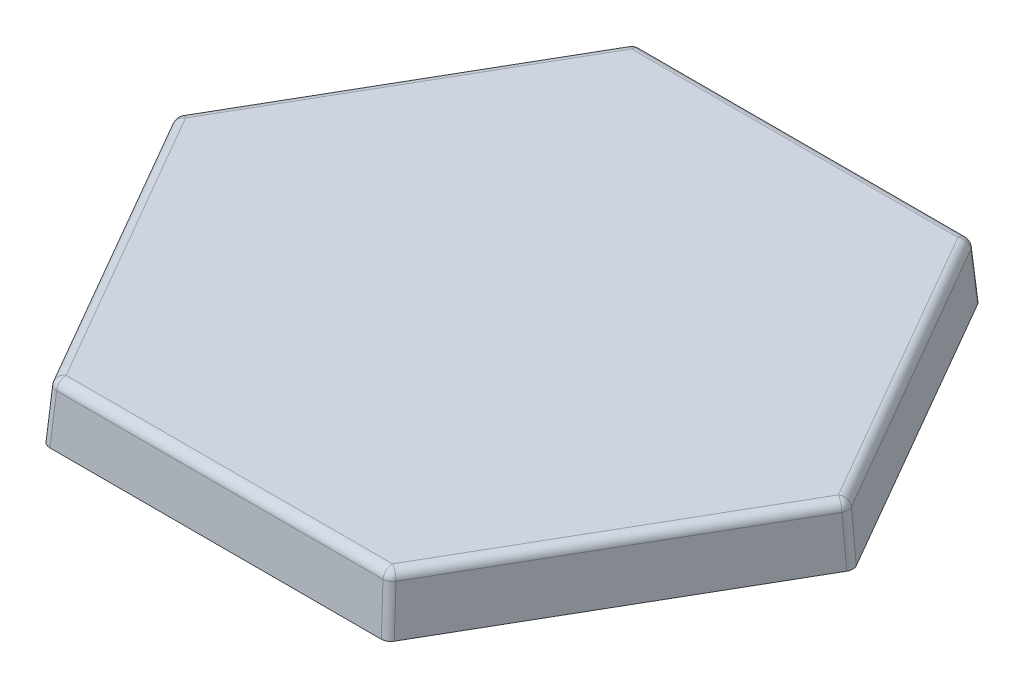
SolidWorks part; units mm, degrees
ref_plane "Front Plane" through (0, 0, 0) normal (0, 0, 1) x (1, 0, 0)
ref_plane "Top Plane" through (0, 0, 0) normal (0, 1, 0) x (1, 0, 0)
ref_plane "Right Plane" through (0, 0, 0) normal (1, 0, 0) x (0, 0, -1)
sketch "Sketch1" plane through (0, 0, 0) normal (0, 1, 0) x (1, 0, 0)
  line L1 (71.8076, 0) -> (35.9038, 62.1872)
  line L2 (35.9038, 62.1872) -> (-35.9038, 62.1872)
  line L3 (-35.9038, 62.1872) -> (-71.8076, 0)
  line L4 (-71.8076, 0) -> (-35.9038, -62.1872)
  line L5 (-35.9038, -62.1872) -> (35.9038, -62.1872)
  line L6 (35.9038, -62.1872) -> (71.8076, 0)
  circle A0 centre (0, 0) radius 62.1872 construction
extrude "Boss-Extrude1" add sketch "Sketch1" along normal blind 12 draft 5
sketch "Sketch2" plane through (0, 0, 0) normal (0, -1, 0) x (1, 0, 0)
  line L1 (68.7047, 0) -> (34.3523, 59.5)
  line L2 (34.3523, 59.5) -> (-34.3523, 59.5)
  line L3 (-34.3523, 59.5) -> (-68.7047, 0)
  line L4 (-68.7047, 0) -> (-34.3523, -59.5)
  line L5 (-34.3523, -59.5) -> (34.3523, -59.5)
  line L6 (34.3523, -59.5) -> (68.7047, 0)
  circle A0 centre (0, 0) radius 59.5 construction
extrude "Cut-Extrude1" cut sketch "Sketch2" against normal blind 10 draft 5
sketch "Sketch3" plane through (0, 0, 0) normal (0, -1, 0) x (1, 0, 0)
  line L1 (70.4367, 0) -> (35.2184, 61)
  line L2 (35.2184, 61) -> (-35.2184, 61)
  line L3 (-35.2184, 61) -> (-70.4367, 0)
  line L4 (-70.4367, 0) -> (-35.2184, -61)
  line L5 (-35.2184, -61) -> (35.2184, -61)
  line L6 (35.2184, -61) -> (70.4367, 0)
  circle A0 centre (0, 0) radius 61 construction
extrude "Cut-Extrude2" cut sketch "Sketch3" against normal blind 1
fillet "Fillet1" radius 2 12 edges at (-35.6007, 6, 61.6623) (35.6007, 6, 61.6623) (71.2015, 6, 0) (35.6007, 6, -61.6623) (-35.6007, 6, -61.6623) (-71.2015, 6, 0) (0, 12, 61.1374) (52.9465, 12, 30.5687) (52.9465, 12, -30.5687) (0, 12, -61.1374) (-52.9465, 12, -30.5687) (-52.9465, 12, 30.5687)
